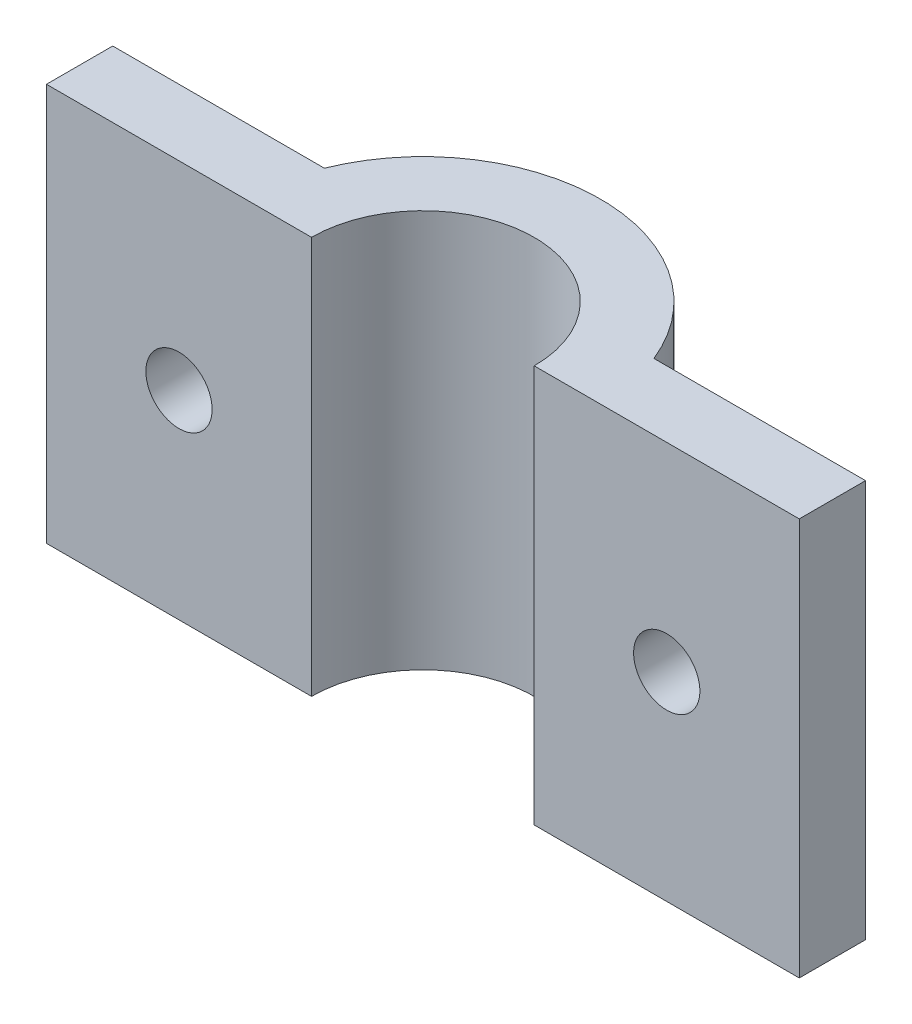
SolidWorks part; units mm, degrees
material "ABS"
ref_plane "Front Plane" through (0, 0, 0) normal (0, 0, 1) x (1, 0, 0)
ref_plane "Top Plane" through (0, 0, 0) normal (0, 1, 0) x (1, 0, 0)
ref_plane "Right Plane" through (0, 0, 0) normal (1, 0, 0) x (0, 0, -1)
sketch "Sketch1" plane through (0, 0, 0) normal (0, 1, 0) x (1, 0, 0)
  line L0 (0, 0) -> (-25.4, 0)
  line L1 (21.336, 0) -> (46.736, 0)
  line L2 (26.4569, 6.35) -> (46.736, 6.35)
  line L3 (-5.1209, 6.35) -> (-25.4, 6.35)
  line L4 (-25.4, 6.35) -> (-25.4, 0)
  line L5 (46.736, 6.35) -> (46.736, 0)
  arc A0 (0, 0) -> (21.336, 0) centre (10.668, 0) cw
  arc A1 (-5.1209, 6.35) -> (26.4569, 6.35) centre (10.668, 0) cw
  dimension "D2" = 10.668
  dimension "D5" = 72.136
  dimension "D1" = 25.4
  dimension "D3" = 21.336
  dimension "D4" = 25.4
  dimension "D6" = 180
  dimension "D7" = 6.35
extrude "Boss-Extrude1" add sketch "Sketch1" along normal blind 38.1
sketch "Sketch2" plane through (0, 0, -6.35) normal (0, 0, -1) x (-1, 0, 0)
  line L0 (5.1209, 0) -> (25.4, 0) construction
  line L2 (25.4, 38.1) -> (25.4, 0) construction
  circle A0 centre (12.7, 19.05) radius 3.175
  point P2 (15.3325, 20.6251)
  point P5 (0, 0)
  point P7 (25.4, 20.0961)
  dimension "D1" = 19.05
  dimension "D3" = 6.35
  dimension "D2" = 12.7
extrude "Cut-Extrude1" cut sketch "Sketch2" against normal blind 38.1
sketch "Sketch3" plane through (0, 0, -6.35) normal (0, 0, -1) x (-1, 0, 0)
  line L0 (-46.736, 38.1) -> (-46.736, 0) construction
  line L1 (-46.736, 0) -> (-26.4569, 0) construction
  circle A0 centre (-34.036, 19.05) radius 3.175
  dimension "D1" = 6.35
  dimension "D2" = 12.7
  dimension "D3" = 19.05
extrude "Cut-Extrude2" cut sketch "Sketch3" against normal through all
